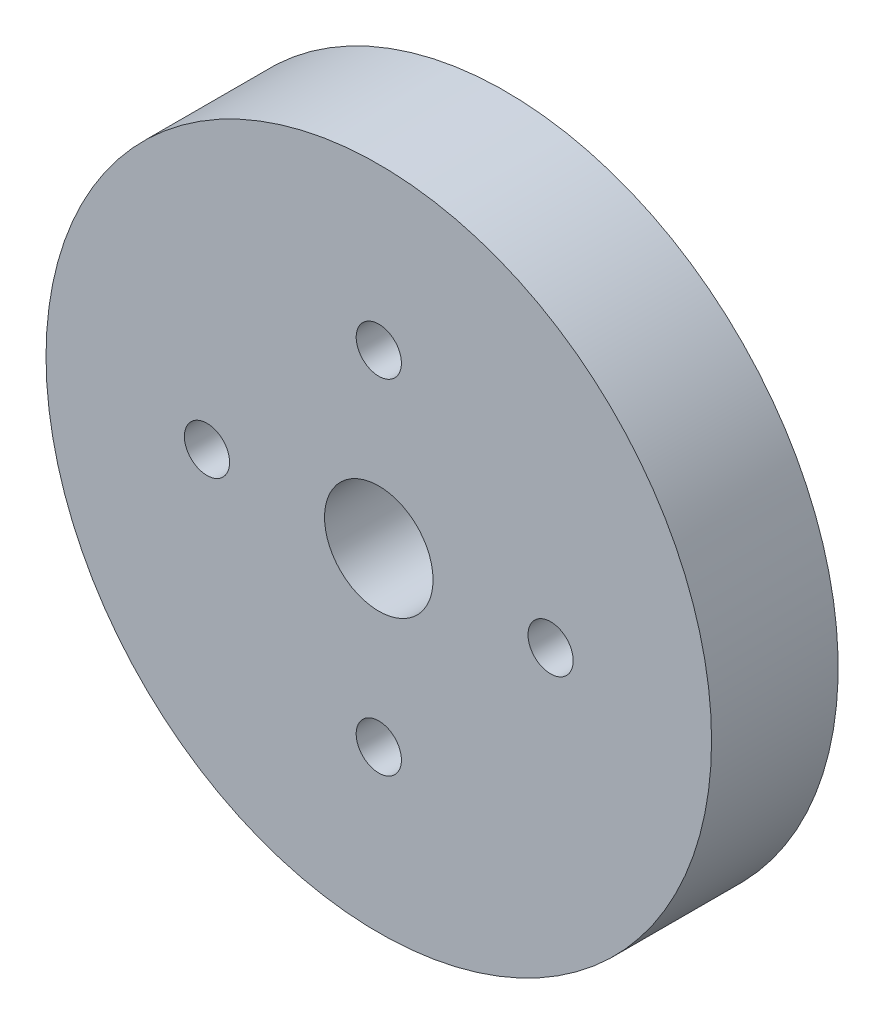
SolidWorks part; units mm, degrees
ref_plane "Alzado" through (0, 0, 0) normal (0, 0, 1) x (1, 0, 0)
ref_plane "Planta" through (0, 0, 0) normal (0, 1, 0) x (1, 0, 0)
ref_plane "Vista lateral" through (0, 0, 0) normal (1, 0, 0) x (0, 0, -1)
sketch "Croquis1" plane through (0, 0, 0) normal (0, 0, 1) x (1, 0, 0)
  circle A0 centre (0, 0) radius 18.4
  dimension "D1" = 36.8
extrude "Saliente-Extruir1" add sketch "Croquis1" along normal blind 26.3
sketch "Croquis2" plane through (0, 0, 26.3) normal (0, 0, 1) x (1, 0, 0)
  circle A0 centre (0, 0) radius 3
  circle A1 centre (0, 0) radius 9.5 construction
  circle A2 centre (0, 9.5) radius 1.25
  circle A3 centre (9.5, 0) radius 1.25
  circle A4 centre (0, -9.5) radius 1.25
  circle A5 centre (-9.5, 0) radius 1.25
  point P15 (0, 0)
  dimension "D1" = 6
  dimension "D2" = 19
  dimension "D3" = 2.5
  dimension "D4" = 4
extrude "Cortar-Extruir1" cut sketch "Croquis2" against normal blind 5
sketch "Croquis3" plane through (0, 0, 0) normal (0, 0, -1) x (-1, 0, 0)
  circle A0 centre (0, 0) radius 10 construction
  circle A1 centre (-10, 0) radius 1.25
  circle A2 centre (0, 10) radius 1.25
  circle A3 centre (10, 0) radius 1.25
  circle A4 centre (0, -10) radius 1.25
  point P14 (0, 0)
  dimension "D1" = 20
  dimension "D2" = 2.5
  dimension "D3" = 4
extrude "Cortar-Extruir2" cut sketch "Croquis3" against normal blind 5
sketch "Croquis7" plane through (0, 0, 0) normal (0, 0, -1) x (-1, 0, 0)
  circle A0 centre (0, 0) radius 18.4
extrude "Cortar-Extruir5" cut sketch "Croquis7" against normal blind 19.3
sketch "Croquis8" plane through (0, 0, 19.3) normal (0, 0, -1) x (-1, 0, 0)
  circle A0 centre (0, 0) radius 6
extrude "Cortar-Extruir6" cut sketch "Croquis8" against normal blind 1
